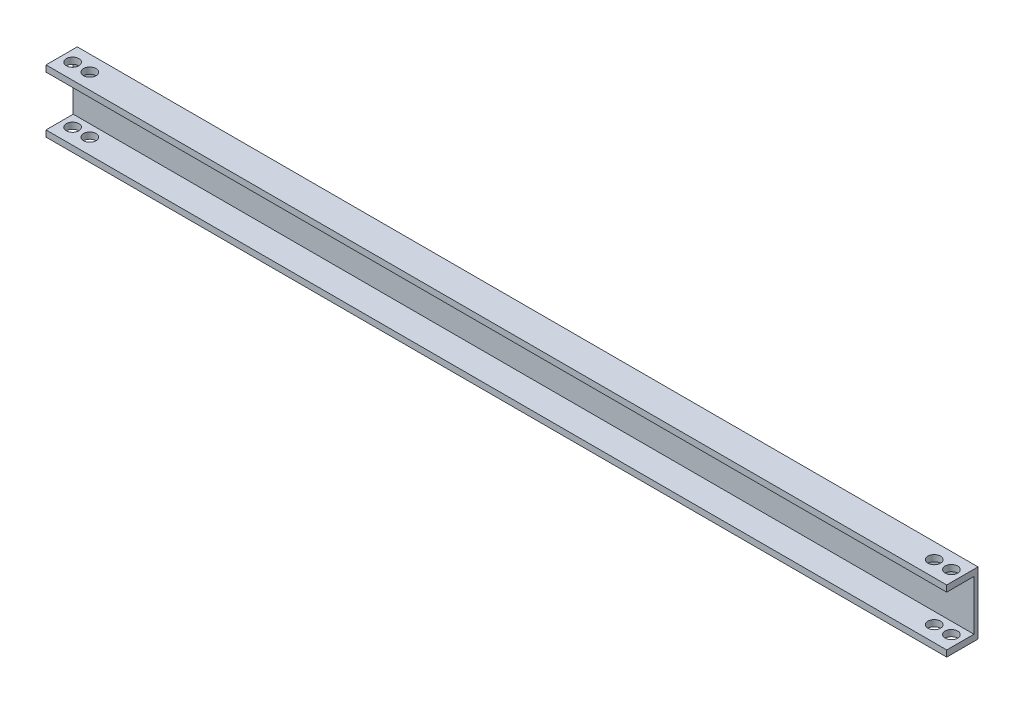
SolidWorks part; units mm, degrees
ref_plane "Front Plane" through (0, 0, 0) normal (0, 0, 1) x (1, 0, 0)
ref_plane "Top Plane" through (0, 0, 0) normal (0, 1, 0) x (1, 0, 0)
ref_plane "Right Plane" through (0, 0, 0) normal (1, 0, 0) x (0, 0, -1)
sketch "Sketch1" plane through (0, 0, 0) normal (0, 1, 0) x (1, 0, 0)
  line L1 (0, 0) -> (731.52, 0)
  line L2 (0, 0) -> (0, 25.4)
  line L3 (0, 25.4) -> (731.52, 25.4)
  line L4 (731.52, 0) -> (731.52, 25.4)
  dimension "D1" = 731.52
  dimension "D2" = 25.4
extrude "Boss-Extrude1" add sketch "Sketch1" along normal blind 50.8
sketch "Sketch2" plane through (0, 50.8, 0) normal (0, 1, 0) x (1, 0, 0)
  circle A0 centre (8.89, 12.7) radius 5.08
  circle A1 centre (22.86, 12.7) radius 5.08
  circle A2 centre (722.63, 12.7) radius 5.08
  circle A3 centre (708.66, 12.7) radius 5.08
  point P8 (0, 0)
  point P9 (0, 0)
  point P10 (0, 0)
  point P11 (0, 0)
  point P12 (0, 0)
extrude "Cut-Extrude1" cut sketch "Sketch2" against normal blind 53.34
sketch "Sketch5" plane through (0, 0, 0) normal (0, 0, 1) x (1, 0, 0)
  line L0 (0, 50.8) -> (0, 0) construction
  line L1 (0, 5.08) -> (731.52, 5.08)
  line L2 (0, 5.08) -> (0, 45.72)
  line L3 (0, 45.72) -> (731.52, 45.72)
  line L4 (731.52, 5.08) -> (731.52, 45.72)
  line L5 (731.52, 50.8) -> (731.52, 0) construction
extrude "Cut-Extrude4" cut sketch "Sketch5" against normal blind 22.098
